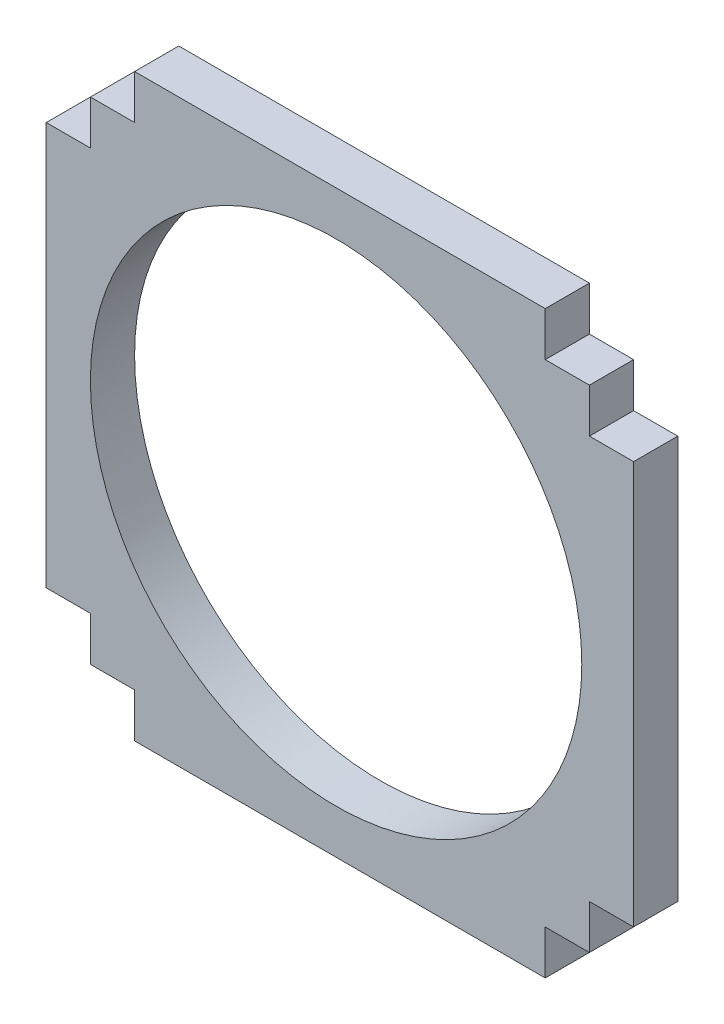
SolidWorks part; units mm, degrees
ref_plane "Front Plane" through (0, 0, 0) normal (0, 0, 1) x (1, 0, 0)
ref_plane "Top Plane" through (0, 0, 0) normal (0, 1, 0) x (1, 0, 0)
ref_plane "Right Plane" through (0, 0, 0) normal (1, 0, 0) x (0, 0, -1)
sketch "Sketch1" plane through (0, 0, 0) normal (0, 0, 1) x (1, 0, 0)
  line L1 (36.4109, 35.3139) -> (30.0609, 35.3139)
  line L2 (36.4109, 35.3139) -> (36.4109, 28.9639)
  line L3 (36.4109, -35.3139) -> (30.0609, -35.3139)
  line L4 (-35.3139, 35.3139) -> (-35.3139, 28.9639)
  line L6 (-35.3139, -28.9639) -> (-35.3139, -35.3139)
  line L7 (-28.9639, 35.3139) -> (-28.9639, 41.6639)
  line L8 (-28.9639, 41.6639) -> (30.0609, 41.6639)
  line L9 (30.0609, 35.3139) -> (30.0609, 41.6639)
  line L10 (-35.3139, 28.9639) -> (-41.6639, 28.9639)
  line L11 (-28.9639, -35.3139) -> (-35.3139, -35.3139)
  line L12 (-35.3139, -28.9639) -> (-41.6639, -28.9639)
  line L13 (-41.6639, 28.9639) -> (-41.6639, -28.9639)
  line L14 (36.4109, -28.9639) -> (36.4109, -35.3139)
  line L15 (-28.9639, -35.3139) -> (-28.9639, -41.6639)
  line L16 (-28.9639, -41.6639) -> (30.0609, -41.6639)
  line L17 (30.0609, -35.3139) -> (30.0609, -41.6639)
  line L19 (36.4109, 66.1906) -> (36.4109, -41.6639) construction
  line L20 (-28.9639, 35.3139) -> (-35.3139, 35.3139)
  line L21 (36.4109, 28.9639) -> (42.7609, 28.9639)
  line L23 (36.4109, -28.9639) -> (42.7609, -28.9639)
  line L24 (42.7609, 28.9639) -> (42.7609, -28.9639)
  circle A0 centre (0, 0) radius 35.1155 construction
  circle A1 centre (0, 0) radius 35.1155 construction
  circle A2 centre (0, 0) radius 35.3139
  dimension "D2" = 6.35
  dimension "D3" = 6.35
  dimension "D1" = 0.1984
extrude "Boss-Extrude1" add sketch "Sketch1" against normal blind 6.35
